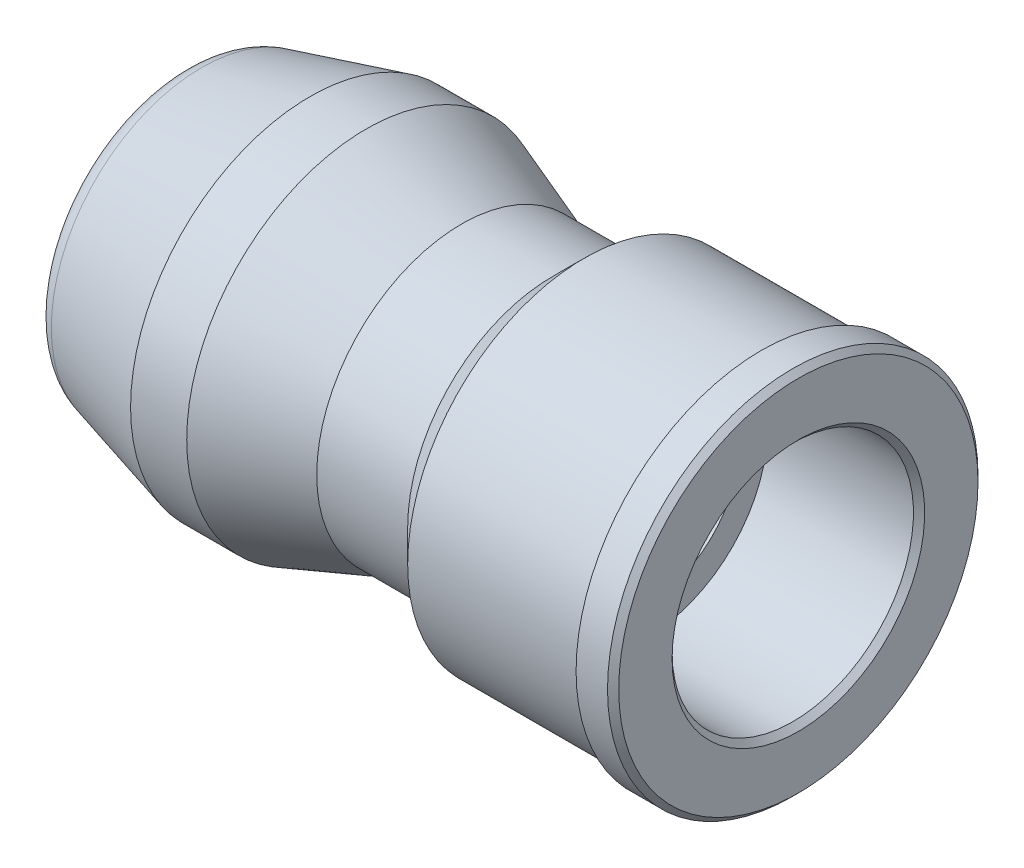
SolidWorks part; units mm, degrees
ref_plane "Front Plane" through (0, 0, 0) normal (0, 0, 1) x (1, 0, 0)
ref_plane "Top Plane" through (0, 0, 0) normal (0, 1, 0) x (1, 0, 0)
ref_plane "Right Plane" through (0, 0, 0) normal (1, 0, 0) x (0, 0, -1)
sketch "Sketch2" plane through (0, 0, 0) normal (0, 0, 1) x (1, 0, 0)
  line L0 (-24.3823, 0) -> (-17.4153, 0)
  line L1 (-24.3823, 0) -> (-24.3823, 2.58)
  line L2 (-24.3823, 2.58) -> (-22.0823, 3.1963)
  line L3 (-22.0823, 3.1963) -> (-21.0823, 3.1963)
  line L4 (-21.0823, 3.1963) -> (-19.3823, 2.58)
  line L13 (-16.0823, 0) -> (-17.4153, 0)
  line L14 (-19.3823, 2.58) -> (-17.7623, 2.58)
  line L15 (-17.7623, 2.58) -> (-17.1923, 3.15)
  line L16 (-17.1923, 3.15) -> (-14.0423, 3.15)
  line L17 (-14.0423, 3.15) -> (-14.0423, 3.3)
  line L18 (-14.0423, 3.3) -> (-13.3823, 3.3)
  line L19 (-13.3823, 3.3) -> (-13.3823, 2.15)
  line L21 (-13.3823, 2.15) -> (-16.0823, 2.15)
  line L23 (-16.0823, 2.15) -> (-16.0823, 0)
  dimension "D1" = 135
  dimension "D2" = 2.58
  dimension "D3" = 105
  dimension "D4" = 2.3
  dimension "D5" = 1.7
  dimension "D6" = 1
  dimension "D7" = 1.62
  dimension "D8" = 3.15
  dimension "D9" = 1.15
  dimension "D10" = 2.15
  dimension "D11" = 2.7
  dimension "D12" = 1
revolve "Revolve1" add sketch "Sketch2" angle 360 about L0
hole_wizard "M4 Tapped Hole1" positions "Sketch4" profile "Sketch3" tap size "M4" standard "ISO" end condition through all
sketch "Sketch4" plane through (-24.3823, 0, 0) normal (-1, 0, 0) x (0, 0, 1)
  point P0 (0, 0)
sketch "Sketch3" plane through (-24.3823, 0, 0) normal (0, 1, 0) x (0, 0, 1)
  line L0 (0, 0) -> (0, 11)
  line L1 (0, 11) -> (1.65, 11)
  line L2 (1.65, 11) -> (1.65, 0.375)
  line L3 (1.65, 0.375) -> (2.025, 0)
  line L5 (2.025, 0) -> (0, 0)
  line L6 (-1.65, 0.375) -> (-2.025, 0) construction
  line L11 (0, -6.35) -> (0, 107.95) construction
  dimension "Thru Tap Drill Dia." = 3.3
  dimension "Thru Tap Drill Depth" = 11
  dimension "Near C'Sink Dia." = 4.05
  dimension "Near C'Sink Angle" = 90
cosmetic thread "Hole Thread1" parameters "D2"=4
fillet "Fillet3" radius 0.5 1 edges at (-24.3823, 0, 2.58)
chamfer "Chamfer1" distance 0.1 angle 45 3 edges at (-13.3823, 0, 3.3) (-14.0423, 0, 3.15) (-13.3823, 0, 2.15)
